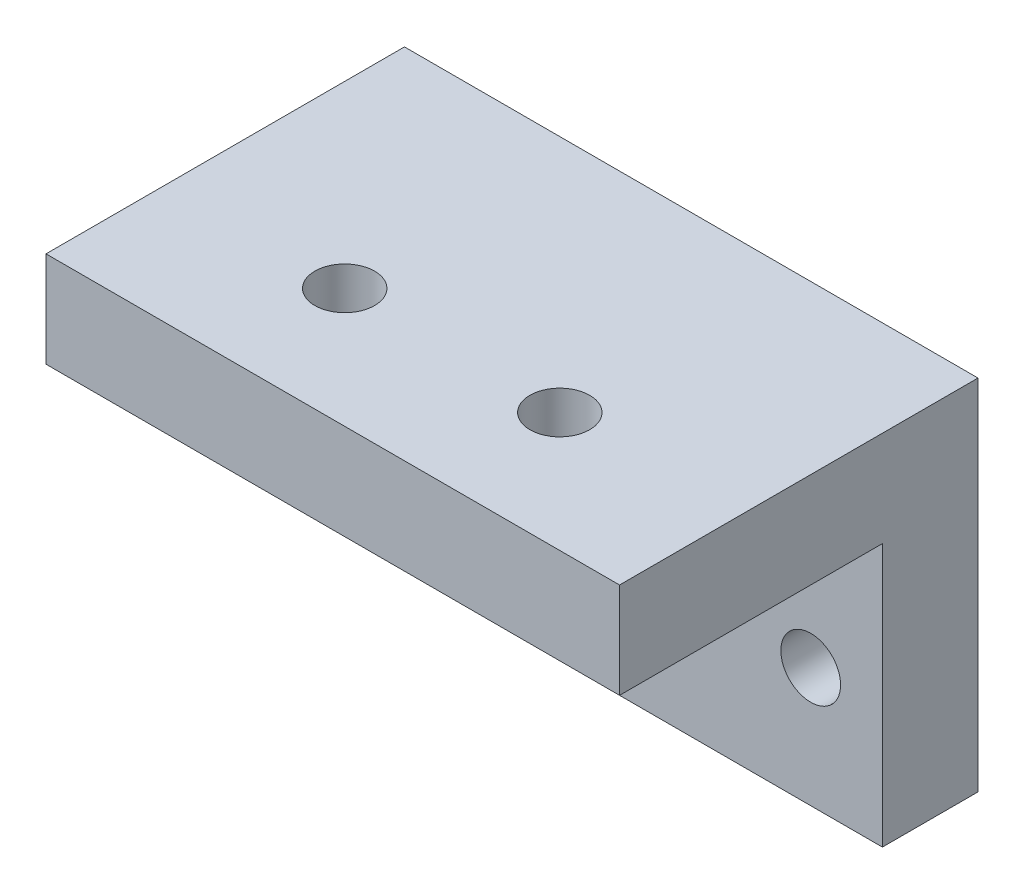
SolidWorks part; units mm, degrees
material "6061-T6 (SS)"
ref_plane "前视基准面" through (0, 0, 0) normal (0, 0, 1) x (1, 0, 0)
ref_plane "上视基准面" through (0, 0, 0) normal (0, 1, 0) x (1, 0, 0)
ref_plane "右视基准面" through (0, 0, 0) normal (1, 0, 0) x (0, 0, -1)
other "Configuration Table"
sketch "草图1" plane through (0, 0, 0) normal (0, 0, 1) x (1, 0, 0)
  line L1 (-12, 7.5) -> (12, 7.5)
  line L2 (-12, 7.5) -> (-12, -7.5)
  line L3 (-12, -7.5) -> (12, -7.5)
  line L4 (12, 7.5) -> (12, -7.5)
  line L5 (-12, 7.5) -> (12, -7.5) construction
  line L6 (-12, -7.5) -> (12, 7.5) construction
  point P0 (0, 0)
  dimension "D1" = 24
  dimension "D2" = 15
extrude "凸台-拉伸1" add sketch "草图1" along normal blind 4
sketch "草图2" plane through (0, 0, 4) normal (0, 0, 1) x (1, 0, 0)
  line L0 (12, -7.5) -> (12, 7.5) construction
  line L1 (-12, 7.5) -> (12, 7.5)
  line L2 (-12, 7.5) -> (-12, 3.5)
  line L3 (-12, 3.5) -> (12, 3.5)
  line L4 (12, 7.5) -> (12, 3.5)
  dimension "D1" = 4
extrude "凸台-拉伸2" add sketch "草图2" along normal blind 11
sketch "草图3" plane through (0, 0, 4) normal (0, 0, 1) x (1, 0, 0)
  line L0 (0, 0) -> (0, -7.5) construction
  line L1 (-12, -7.5) -> (12, -7.5) construction
  line L2 (12, -7.5) -> (12, 3.5) construction
  circle A0 centre (-9, -2.5) radius 1.25
  circle A1 centre (9, -2.5) radius 1.25
  dimension "D2" = 2.5
  dimension "D1" = 3
  dimension "D3" = 5
extrude "切除-拉伸1" cut sketch "草图3" against normal through all
cosmetic thread "装饰螺纹线1" parameters "D2"=3
cosmetic thread "装饰螺纹线2" parameters "D2"=3
sketch "草图4" plane through (0, 3.5, 0) normal (0, -1, 0) x (1, 0, 0)
  line L0 (0, 15) -> (0, 4) construction
  line L1 (-12, 15) -> (12, 15) construction
  line L2 (-12, 4) -> (12, 4) construction
  line L3 (-12, 15) -> (-12, 4) construction
  circle A0 centre (-4.5, 10) radius 1.25
  circle A1 centre (4.5, 10) radius 1.25
  dimension "D1" = 2.5
  dimension "D2" = 5
  dimension "D3" = 7.5
extrude "切除-拉伸2" cut sketch "草图4" against normal through all
cosmetic thread "装饰螺纹线3" parameters "D2"=3
cosmetic thread "装饰螺纹线4" parameters "D2"=3
